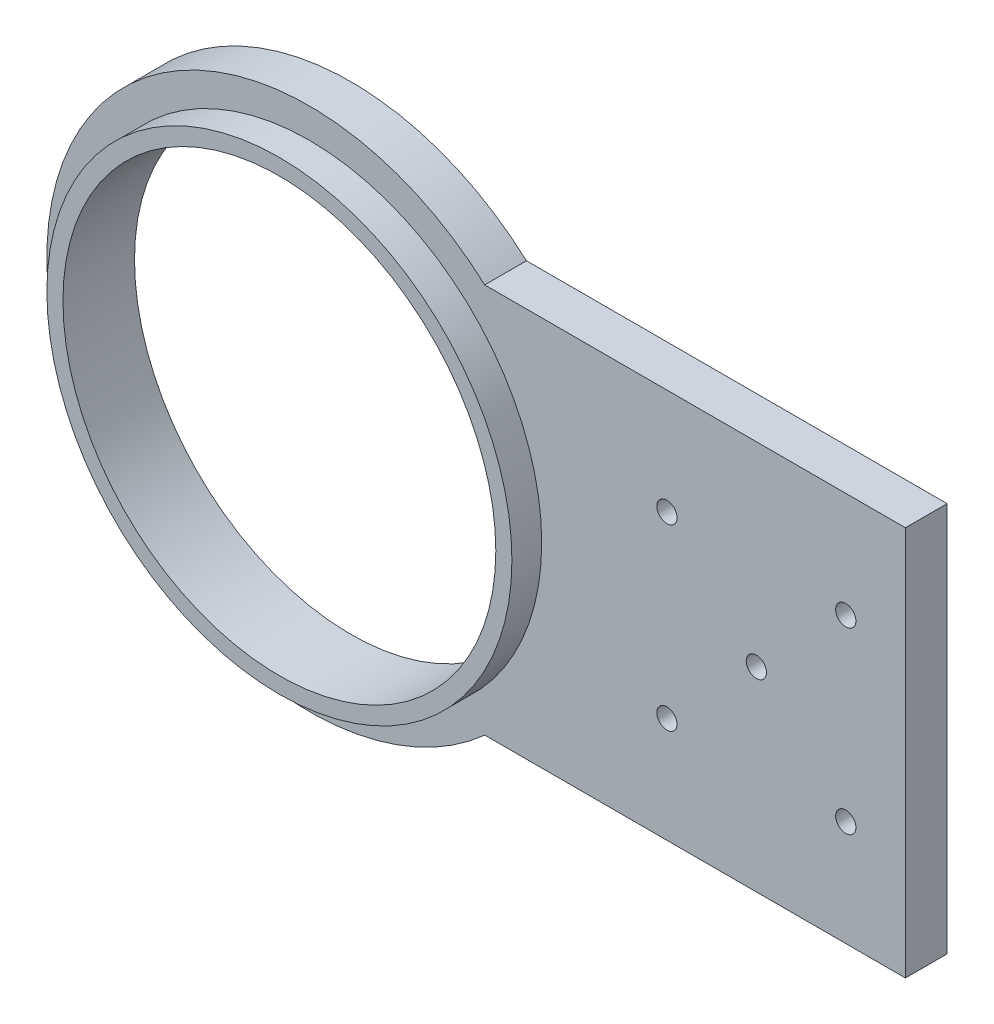
SolidWorks part; units mm, degrees
material "6063-T5"
ref_plane "Front" through (0, 0, 0) normal (0, 0, 1) x (1, 0, 0)
ref_plane "Top" through (0, 0, 0) normal (0, 1, 0) x (1, 0, 0)
ref_plane "Right" through (0, 0, 0) normal (1, 0, 0) x (0, 0, -1)
sketch "Croquis1" plane through (0, 0, 0) normal (0, 0, 1) x (1, 0, 0)
  circle A0 centre (0, 0) radius 36.3
  circle A1 centre (0, 0) radius 39
  dimension "D1" = 72.6
  dimension "D2" = 78
extrude "Saliente-Extruir1" add sketch "Croquis1" along normal mid plane 5
sketch "Croquis2" plane through (0, 0, -2.5) normal (0, 0, -1) x (-1, 0, 0)
  circle A0 centre (0, 0) radius 44
  circle A1 centre (0, 0) radius 36.3 construction
  circle A2 centre (0, 0) radius 36.3
  dimension "D1" = 88
extrude "Saliente-Extruir2" add sketch "Croquis2" along normal blind 7
sketch "Croquis3" plane through (0, 0, -9.5) normal (0, 0, -1) x (-1, 0, 0)
  line L0 (-29.4399, 32.7) -> (-100, 32.7)
  line L1 (-100, 32.7) -> (-100, -32.7)
  line L2 (-100, -32.7) -> (-29.4399, -32.7)
  line L3 (6.6, 0) -> (-6.6, 0) construction
  line L4 (0, 6.6) -> (0, -6.6) construction
  circle A0 centre (0, 0) radius 44 construction
  arc A1 (-29.4399, 32.7) -> (-29.4399, -32.7) centre (0, 0) ccw
  point P10 (-100, 0)
  circle M3 centre (0, 0) radius 44
  dimension "D1" = 65.4
  dimension "D2" = 100
extrude "Saliente-Extruir3" add sketch "Croquis3" against normal blind 7 contours L1 L2 L0 M3
hole_wizard "Refrentado para tornillo con cabeza troncocónica de M31" positions "Croquis4" profile "Croquis6" counterbore size "M3" standard "Ansi Metric" end condition up to next
sketch "Croquis4" plane through (0, 0, -9.5) normal (0, 0, -1) x (-1, 0, 0)
  line L1 (-60, -15) -> (-90, -15) construction
  line L2 (-60, -15) -> (-60, 15) construction
  line L3 (-60, 15) -> (-90, 15) construction
  line L4 (-90, -15) -> (-90, 15) construction
  line L5 (-60, -15) -> (-90, 15) construction
  line L6 (-60, 15) -> (-90, -15) construction
  line L7 (6.6, 0) -> (-6.6, 0) construction
  line L8 (-100, 32.7) -> (-100, -32.7) construction
  point P1 (-75, 0)
  point P2 (-90, 15)
  point P29 (-60, -15)
  point P30 (-60, 15)
  point P31 (-90, -15)
  dimension "D1" = 30
  dimension "D2" = 25
sketch "Croquis6" plane through (75, 0, -9.5) normal (1, 0, 0) x (0, 1, 0)
  line L0 (0, 0) -> (0, 7)
  line L1 (0, 7) -> (1.7, 7)
  line L3 (1.7, 7) -> (1.7, 2.4)
  line L4 (1.7, 2.4) -> (3.5, 2.4)
  line L5 (3.5, 2.4) -> (3.5, 0)
  line L7 (3.5, 0) -> (0, 0)
  line L11 (0, -6.35) -> (0, 107.95) construction
  dimension "Diámetro de taladro hasta el siguiente" = 3.4
  dimension "Profundidad de taladro hasta el siguiente" = 7
  dimension "Diámetro de refrentado" = 7
  dimension "Profundidad de refrentado" = 2.4
